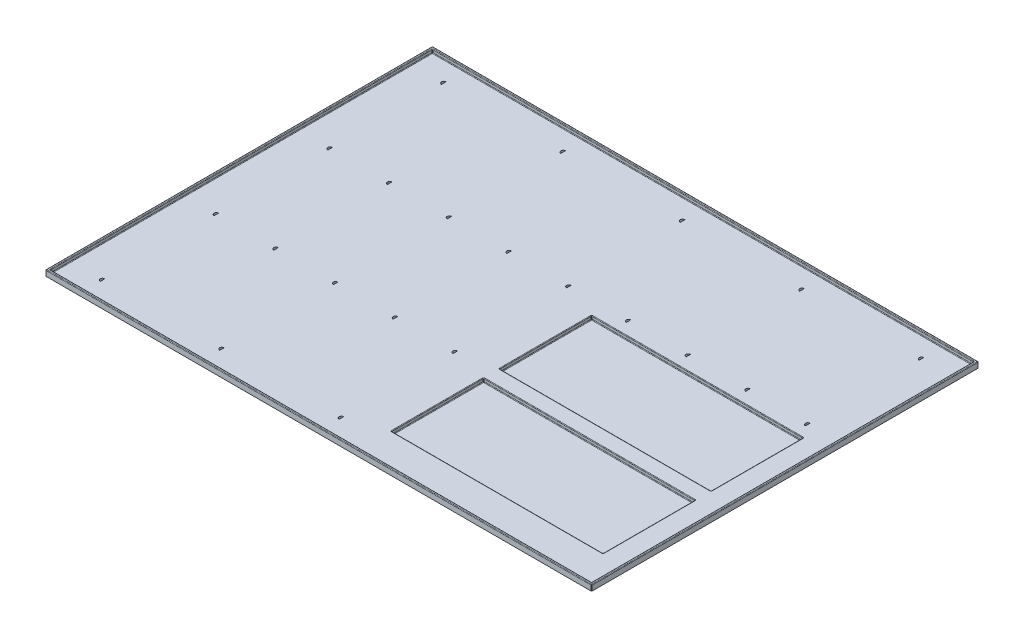
SolidWorks part; units mm, degrees
material "201 Annealed Stainless Steel (SS)"
ref_plane "Front Plane" through (0, 0, 0) normal (0, 0, 1) x (1, 0, 0)
ref_plane "Top Plane" through (0, 0, 0) normal (0, 1, 0) x (1, 0, 0)
ref_plane "Right Plane" through (0, 0, 0) normal (1, 0, 0) x (0, 0, -1)
sketch "Sketch1" plane through (0, 0, 0) normal (0, 1, 0) x (1, 0, 0)
  line L1 (0, 0) -> (609.6, 0)
  line L2 (0, 0) -> (0, 431.8)
  line L3 (0, 431.8) -> (609.6, 431.8)
  line L4 (609.6, 0) -> (609.6, 431.8)
  dimension "D1" = 431.8
  dimension "D2" = 609.6
extrude "Tray Base" add sketch "Sketch1" along normal blind 6.35 contours L2 L3 L4 L1
ref_plane "Plane1" through (0, -3.81, 0) normal (0, -1, 0) x (-1, 0, 0)
sketch "Sketch8" plane through (0, -3.81, 0) normal (0, -1, 0) x (-1, 0, 0)
  line L0 (-633.0611, 152.4) -> (73.8203, 152.4) construction
  line L1 (-584.2, 158.75) -> (-342.9, 158.75)
  line L2 (-584.2, 158.75) -> (-584.2, 266.7)
  line L3 (-584.2, 266.7) -> (-342.9, 266.7)
  line L4 (-342.9, 158.75) -> (-342.9, 266.7)
  line L5 (-584.2, 146.05) -> (-342.9, 146.05)
  line L6 (-342.9, 146.05) -> (-342.9, 38.1)
  line L7 (-584.2, 38.1) -> (-342.9, 38.1)
  line L8 (-584.2, 146.05) -> (-584.2, 38.1)
  dimension "D1" = 158.75
  dimension "D2" = 266.7
  dimension "D3" = 584.2
  dimension "D4" = 342.9
  dimension "D5" = 152.4
extrude "Square Indent" add sketch "Sketch8" against normal through all contours L2 L3 L4 L1 | L5 L6 L7 L8
shell "Shell2" thickness 2.54
sketch "Sketch32" plane through (0, 0, 0) normal (0, 1, 0) x (1, 0, 0)
  line L0 (38.1, 27.94) -> (38.1, 22.86)
  line L1 (38.1, 154.94) -> (38.1, 149.86)
  line L2 (38.1, 281.94) -> (38.1, 276.86)
  line L3 (38.1, 408.94) -> (38.1, 403.86)
  line L4 (171.45, 27.94) -> (171.45, 22.86)
  line L5 (304.8, 27.94) -> (304.8, 22.86)
  line L6 (104.775, 154.94) -> (104.775, 149.86)
  line L7 (171.45, 154.94) -> (171.45, 149.86)
  line L8 (238.125, 154.94) -> (238.125, 149.86)
  line L9 (304.8, 154.94) -> (304.8, 149.86)
  line L10 (104.775, 281.94) -> (104.775, 276.86)
  line L11 (171.45, 281.94) -> (171.45, 276.86)
  line L12 (238.125, 281.94) -> (238.125, 276.86)
  line L13 (304.8, 281.94) -> (304.8, 276.86)
  line L14 (371.475, 281.94) -> (371.475, 276.86)
  line L15 (438.15, 281.94) -> (438.15, 276.86)
  line L16 (504.825, 281.94) -> (504.825, 276.86)
  line L17 (571.5, 281.94) -> (571.5, 276.86)
  line L19 (171.45, 408.94) -> (171.45, 403.86)
  line L20 (304.8, 408.94) -> (304.8, 403.86)
  line L21 (438.15, 408.94) -> (438.15, 403.86)
  line L22 (571.5, 408.94) -> (571.5, 403.86)
  arc A0 (38.1, 27.94) -> (38.1, 22.86) centre (38.1, 25.4) ccw
  arc A50 (38.1, 154.94) -> (38.1, 149.86) centre (38.1, 152.4) ccw
  arc A51 (38.1, 281.94) -> (38.1, 276.86) centre (38.1, 279.4) ccw
  arc A52 (38.1, 408.94) -> (38.1, 403.86) centre (38.1, 406.4) ccw
  arc A53 (171.45, 27.94) -> (171.45, 22.86) centre (171.45, 25.4) ccw
  arc A54 (304.8, 27.94) -> (304.8, 22.86) centre (304.8, 25.4) ccw
  arc A55 (104.775, 154.94) -> (104.775, 149.86) centre (104.775, 152.4) ccw
  arc A56 (171.45, 154.94) -> (171.45, 149.86) centre (171.45, 152.4) ccw
  arc A57 (238.125, 154.94) -> (238.125, 149.86) centre (238.125, 152.4) ccw
  arc A58 (304.8, 154.94) -> (304.8, 149.86) centre (304.8, 152.4) ccw
  arc A59 (104.775, 281.94) -> (104.775, 276.86) centre (104.775, 279.4) ccw
  arc A65 (171.45, 281.94) -> (171.45, 276.86) centre (171.45, 279.4) ccw
  arc A66 (238.125, 281.94) -> (238.125, 276.86) centre (238.125, 279.4) ccw
  arc A67 (304.8, 281.94) -> (304.8, 276.86) centre (304.8, 279.4) ccw
  arc A70 (371.475, 281.94) -> (371.475, 276.86) centre (371.475, 279.4) ccw
  arc A71 (438.15, 281.94) -> (438.15, 276.86) centre (438.15, 279.4) ccw
  arc A77 (504.825, 281.94) -> (504.825, 276.86) centre (504.825, 279.4) ccw
  arc A78 (571.5, 281.94) -> (571.5, 276.86) centre (571.5, 279.4) ccw
  arc A80 (171.45, 408.94) -> (171.45, 403.86) centre (171.45, 406.4) ccw
  arc A81 (304.8, 408.94) -> (304.8, 403.86) centre (304.8, 406.4) ccw
  arc A82 (438.15, 408.94) -> (438.15, 403.86) centre (438.15, 406.4) ccw
  arc A83 (571.5, 408.94) -> (571.5, 403.86) centre (571.5, 406.4) ccw
  dimension "D1" = 5.08
  dimension "D12" = 133.35
  dimension "D5" = 152.4
  dimension "D7" = 5
  dimension "D10" = 66.675
  dimension "D8" = 66.675
  dimension "D2" = 38.1
  dimension "D3" = 25.4
  dimension "D6" = 171.45
  dimension "D9" = 9
  dimension "D11" = 5
  dimension "D4" = 4
extrude "Cut-Extrude1" cut sketch "Sketch32" against normal through all both and the other way through all
sketch "Sketch34" plane through (0, 0, 0) normal (0, -1, 0) x (1, 0, 0)
  line L0 (304.8, -366.494) -> (304.8, 97.2958) construction
  line L1 (-50.7398, -215.9) -> (666.788, -215.9) construction
  circle A0 centre (12.7, -12.7) radius 3.175
  circle A1 centre (596.9, -12.7) radius 3.175
  circle A2 centre (596.9, -419.1) radius 3.175
  circle A3 centre (12.7, -419.1) radius 3.175
  dimension "D1" = 6.35
  dimension "D2" = 12.7
  dimension "D3" = 12.7
  dimension "D4" = 304.8
  dimension "D5" = 215.9
extrude "Boss-Extrude1" add sketch "Sketch34" along normal blind 3.81
fillet "Fillet1" radius 0.635 56 edges at (2.54, 2.54, -215.9) (2.54, 4.445, -2.54) (304.8, 2.54, -2.54) (607.06, 4.445, -2.54) (607.06, 2.54, -215.9) (0, 6.35, -215.9) (304.8, 6.35, -431.8) (609.6, 6.35, -215.9) (304.8, 6.35, 0) (607.06, 6.35, -215.9) (2.54, 6.35, -215.9) (304.8, 6.35, -2.54) (2.54, 4.445, -429.26) (304.8, 6.35, -429.26) (607.06, 4.445, -429.26) (304.8, 2.54, -429.26) (609.6, 3.175, 0) (0, 3.175, -431.8) (609.6, 3.175, -431.8) (0, 3.175, 0) (581.66, 2.54, -212.725) (463.55, 2.54, -264.16) (581.66, 0.635, -264.16) (463.55, 2.54, -143.51) (345.44, 2.54, -92.075) (345.44, 0.635, -143.51) (345.44, 0.635, -264.16) (345.44, 2.54, -212.725) (345.44, 0.635, -40.64) (463.55, 2.54, -40.64) (581.66, 0.635, -40.64) (581.66, 0.635, -143.51) (581.66, 2.54, -92.075) (345.44, 0.635, -161.29) (581.66, 0.635, -161.29) (463.55, 2.54, -161.29) (463.55, -1.27, -40.64) (345.44, -1.27, -92.075) (463.55, -1.27, -143.51) (581.66, -1.27, -92.075) (345.44, -1.27, -212.725) (463.55, -1.27, -264.16) (581.66, -1.27, -212.725) (463.55, -1.27, -161.29) (584.2, -3.81, -212.725) (463.55, -3.81, -266.7) (342.9, -3.81, -212.725) (463.55, -3.81, -158.75) (463.55, -3.81, -146.05) (342.9, -3.81, -92.075) (463.55, -3.81, -38.1) (584.2, -3.81, -92.075) (12.7, -3.81, -15.875) (596.9, -3.81, -9.525) (596.9, -3.81, -422.275) (12.7, -3.81, -415.925)
